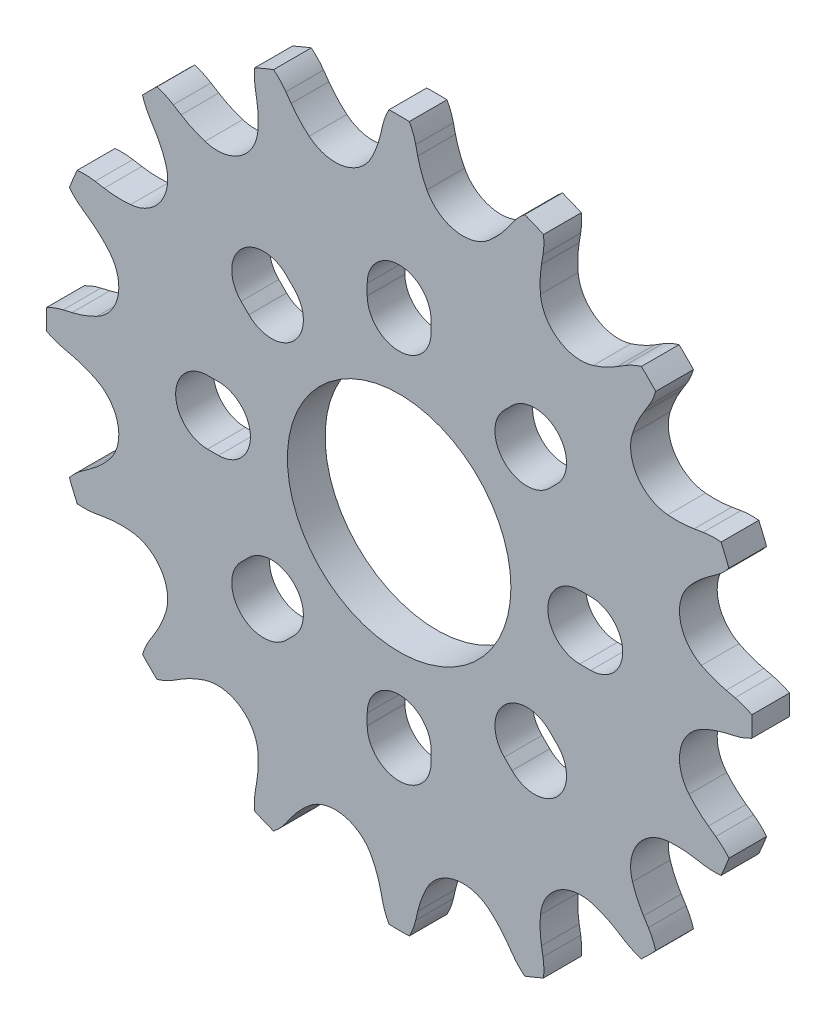
SolidWorks part; units mm, degrees
ref_plane "Front" through (0, 0, 0) normal (0, 0, 1) x (1, 0, 0)
ref_plane "Top" through (0, 0, 0) normal (0, 1, 0) x (1, 0, 0)
ref_plane "Right" through (0, 0, 0) normal (1, 0, 0) x (0, 0, -1)
ref_plane "Plane1" through (0, 0, -0.3201) normal (0, 0, -1) x (-1, 0, 0)
sketch "Sketch1" plane through (0, 0, -0.3201) normal (0, 0, -1) x (-1, 0, 0)
  line L0 (19.3696, 6.7618) -> (19.8362, 7.0946)
  line L1 (19.043, 9.0096) -> (18.4777, 8.9151)
  line L2 (15.3075, 13.6595) -> (15.6113, 14.1456)
  line L3 (14.1456, 15.6113) -> (13.6595, 15.3075)
  line L4 (8.9151, 18.4777) -> (9.0096, 19.043)
  line L5 (7.0946, 19.8362) -> (6.7618, 19.3696)
  line L6 (1.1653, 20.4828) -> (1.0364, 21.0412)
  line L7 (-1.0364, 21.0412) -> (-1.1653, 20.4828)
  line L8 (-6.7618, 19.3696) -> (-7.0946, 19.8362)
  line L9 (-9.0096, 19.043) -> (-8.9151, 18.4777)
  line L10 (-13.6595, 15.3075) -> (-14.1456, 15.6113)
  line L11 (-15.6113, 14.1456) -> (-15.3075, 13.6595)
  line L12 (-18.4777, 8.9151) -> (-19.043, 9.0096)
  line L13 (-19.8362, 7.0946) -> (-19.3696, 6.7618)
  line L14 (-20.4828, 1.1653) -> (-21.0412, 1.0364)
  line L15 (-21.0412, -1.0364) -> (-20.4828, -1.1653)
  line L16 (-19.3696, -6.7618) -> (-19.8362, -7.0946)
  line L17 (-19.043, -9.0096) -> (-18.4777, -8.9151)
  line L18 (-15.3075, -13.6595) -> (-15.6113, -14.1456)
  line L19 (-14.1456, -15.6113) -> (-13.6595, -15.3075)
  line L20 (-8.9151, -18.4777) -> (-9.0096, -19.043)
  line L21 (-7.0946, -19.8362) -> (-6.7618, -19.3696)
  line L22 (-1.1653, -20.4828) -> (-1.0364, -21.0412)
  line L23 (1.0364, -21.0412) -> (1.1653, -20.4828)
  line L24 (6.7618, -19.3696) -> (7.0946, -19.8362)
  line L25 (9.0096, -19.043) -> (8.9151, -18.4777)
  line L26 (13.6595, -15.3075) -> (14.1456, -15.6113)
  line L27 (15.6113, -14.1456) -> (15.3075, -13.6595)
  line L28 (18.4777, -8.9151) -> (19.043, -9.0096)
  line L29 (19.8362, -7.0946) -> (19.3696, -6.7618)
  line L30 (20.4828, -1.1653) -> (21.0412, -1.0364)
  line L31 (21.0412, 1.0364) -> (20.4828, 1.1653)
  line L32 (-2, 11.3137) -> (-2, 12)
  line L33 (2, 12) -> (2, 11.3137)
  line L34 (6.5858, 9.4142) -> (7.0711, 9.8995)
  line L35 (9.8995, 7.0711) -> (9.4142, 6.5858)
  line L36 (-9.4142, 6.5858) -> (-9.8995, 7.0711)
  line L37 (-7.0711, 9.8995) -> (-6.5858, 9.4142)
  line L38 (-11.3137, -2) -> (-12, -2)
  line L39 (-12, 2) -> (-11.3137, 2)
  line L40 (-9.8995, -7.0711) -> (-9.4142, -6.5858)
  line L41 (-6.5858, -9.4142) -> (-7.0711, -9.8995)
  line L42 (2, -11.3137) -> (2, -12)
  line L43 (-2, -12) -> (-2, -11.3137)
  line L44 (9.4142, -6.5858) -> (9.8995, -7.0711)
  line L45 (7.0711, -9.8995) -> (6.5858, -9.4142)
  line L46 (11.3137, 2) -> (12, 2)
  line L47 (12, -2) -> (11.3137, -2)
  arc A0 (18.1555, 5.6395) -> (19.3696, 6.7618) centre (23.1735, 1.4288) cw
  arc A1 (19.8362, 7.0946) -> (20.6534, 7.8644) centre (17.4306, 10.4672) ccw
  arc A2 (20.6534, 7.8644) -> (20.1651, 9.0432) centre (0, 0) ccw
  arc A3 (20.1651, 9.0432) -> (19.043, 9.0096) centre (19.7267, 4.9239) ccw
  arc A4 (18.4777, 8.9151) -> (16.8256, 8.8501) centre (17.3965, 15.3758) cw
  arc A5 (16.8256, 8.8501) -> (14.6153, 12.158) centre (17.0479, 11.391) cw
  arc A6 (14.6153, 12.158) -> (15.3075, 13.6595) centre (20.8628, 10.1882) cw
  arc A7 (15.6113, 14.1456) -> (16.0717, 15.1694) centre (12.0981, 16.3408) ccw
  arc A8 (16.0717, 15.1694) -> (15.1694, 16.0717) centre (0, 0) ccw
  arc A9 (15.1694, 16.0717) -> (14.1456, 15.6113) centre (16.3408, 12.0981) ccw
  arc A10 (13.6595, 15.3075) -> (12.158, 14.6153) centre (10.1882, 20.8628) cw
  arc A11 (12.158, 14.6153) -> (8.8501, 16.8256) centre (11.391, 17.0479) cw
  arc A12 (8.8501, 16.8256) -> (8.9151, 18.4777) centre (15.3758, 17.3965) cw
  arc A13 (9.0096, 19.043) -> (9.0432, 20.1651) centre (4.9239, 19.7267) ccw
  arc A14 (9.0432, 20.1651) -> (7.8644, 20.6534) centre (0, 0) ccw
  arc A15 (7.8644, 20.6534) -> (7.0946, 19.8362) centre (10.4672, 17.4306) ccw
  arc A16 (6.7618, 19.3696) -> (5.6395, 18.1555) centre (1.4288, 23.1735) cw
  arc A17 (5.6395, 18.1555) -> (1.7376, 18.9316) centre (4, 20.1094) cw
  arc A18 (1.7376, 18.9316) -> (1.1653, 20.4828) centre (7.548, 21.9564) cw
  arc A19 (1.0364, 21.0412) -> (0.638, 22.0908) centre (-3, 20.1094) ccw
  arc A20 (0.638, 22.0908) -> (-0.638, 22.0908) centre (0, 0) ccw
  arc A21 (-0.638, 22.0908) -> (-1.0364, 21.0412) centre (3, 20.1094) ccw
  arc A22 (-1.1653, 20.4828) -> (-1.7376, 18.9316) centre (-7.548, 21.9564) cw
  arc A23 (-1.7376, 18.9316) -> (-5.6395, 18.1555) centre (-4, 20.1094) cw
  arc A24 (-5.6395, 18.1555) -> (-6.7618, 19.3696) centre (-1.4288, 23.1735) cw
  arc A25 (-7.0946, 19.8362) -> (-7.8644, 20.6534) centre (-10.4672, 17.4306) ccw
  arc A26 (-7.8644, 20.6534) -> (-9.0432, 20.1651) centre (0, 0) ccw
  arc A27 (-9.0432, 20.1651) -> (-9.0096, 19.043) centre (-4.9239, 19.7267) ccw
  arc A28 (-8.9151, 18.4777) -> (-8.8501, 16.8256) centre (-15.3758, 17.3965) cw
  arc A29 (-8.8501, 16.8256) -> (-12.158, 14.6153) centre (-11.391, 17.0479) cw
  arc A30 (-12.158, 14.6153) -> (-13.6595, 15.3075) centre (-10.1882, 20.8628) cw
  arc A31 (-14.1456, 15.6113) -> (-15.1694, 16.0717) centre (-16.3408, 12.0981) ccw
  arc A32 (-15.1694, 16.0717) -> (-16.0717, 15.1694) centre (0, 0) ccw
  arc A33 (-16.0717, 15.1694) -> (-15.6113, 14.1456) centre (-12.0981, 16.3408) ccw
  arc A34 (-15.3075, 13.6595) -> (-14.6153, 12.158) centre (-20.8628, 10.1882) cw
  arc A35 (-14.6153, 12.158) -> (-16.8256, 8.8501) centre (-17.0479, 11.391) cw
  arc A36 (-16.8256, 8.8501) -> (-18.4777, 8.9151) centre (-17.3965, 15.3758) cw
  arc A37 (-19.043, 9.0096) -> (-20.1651, 9.0432) centre (-19.7267, 4.9239) ccw
  arc A38 (-20.1651, 9.0432) -> (-20.6534, 7.8644) centre (0, 0) ccw
  arc A39 (-20.6534, 7.8644) -> (-19.8362, 7.0946) centre (-17.4306, 10.4672) ccw
  arc A40 (-19.3696, 6.7618) -> (-18.1555, 5.6395) centre (-23.1735, 1.4288) cw
  arc A41 (-18.1555, 5.6395) -> (-18.9316, 1.7376) centre (-20.1094, 4) cw
  arc A42 (-18.9316, 1.7376) -> (-20.4828, 1.1653) centre (-21.9564, 7.548) cw
  arc A43 (-21.0412, 1.0364) -> (-22.0908, 0.638) centre (-20.1094, -3) ccw
  arc A44 (-22.0908, 0.638) -> (-22.0908, -0.638) centre (0, 0) ccw
  arc A45 (-22.0908, -0.638) -> (-21.0412, -1.0364) centre (-20.1094, 3) ccw
  arc A46 (-20.4828, -1.1653) -> (-18.9316, -1.7376) centre (-21.9564, -7.548) cw
  arc A47 (-18.9316, -1.7376) -> (-18.1555, -5.6395) centre (-20.1094, -4) cw
  arc A48 (-18.1555, -5.6395) -> (-19.3696, -6.7618) centre (-23.1735, -1.4288) cw
  arc A49 (-19.8362, -7.0946) -> (-20.6534, -7.8644) centre (-17.4306, -10.4672) ccw
  arc A50 (-20.6534, -7.8644) -> (-20.1651, -9.0432) centre (0, 0) ccw
  arc A51 (-20.1651, -9.0432) -> (-19.043, -9.0096) centre (-19.7267, -4.9239) ccw
  arc A52 (-18.4777, -8.9151) -> (-16.8256, -8.8501) centre (-17.3965, -15.3758) cw
  arc A53 (-16.8256, -8.8501) -> (-14.6153, -12.158) centre (-17.0479, -11.391) cw
  arc A54 (-14.6153, -12.158) -> (-15.3075, -13.6595) centre (-20.8628, -10.1882) cw
  arc A55 (-15.6113, -14.1456) -> (-16.0717, -15.1694) centre (-12.0981, -16.3408) ccw
  arc A56 (-16.0717, -15.1694) -> (-15.1694, -16.0717) centre (0, 0) ccw
  arc A57 (-15.1694, -16.0717) -> (-14.1456, -15.6113) centre (-16.3408, -12.0981) ccw
  arc A58 (-13.6595, -15.3075) -> (-12.158, -14.6153) centre (-10.1882, -20.8628) cw
  arc A59 (-12.158, -14.6153) -> (-8.8501, -16.8256) centre (-11.391, -17.0479) cw
  arc A60 (-8.8501, -16.8256) -> (-8.9151, -18.4777) centre (-15.3758, -17.3965) cw
  arc A61 (-9.0096, -19.043) -> (-9.0432, -20.1651) centre (-4.9239, -19.7267) ccw
  arc A62 (-9.0432, -20.1651) -> (-7.8644, -20.6534) centre (0, 0) ccw
  arc A63 (-7.8644, -20.6534) -> (-7.0946, -19.8362) centre (-10.4672, -17.4306) ccw
  arc A64 (-6.7618, -19.3696) -> (-5.6395, -18.1555) centre (-1.4288, -23.1735) cw
  arc A65 (-5.6395, -18.1555) -> (-1.7376, -18.9316) centre (-4, -20.1094) cw
  arc A66 (-1.7376, -18.9316) -> (-1.1653, -20.4828) centre (-7.548, -21.9564) cw
  arc A67 (-1.0364, -21.0412) -> (-0.638, -22.0908) centre (3, -20.1094) ccw
  arc A68 (-0.638, -22.0908) -> (0.638, -22.0908) centre (0, 0) ccw
  arc A69 (0.638, -22.0908) -> (1.0364, -21.0412) centre (-3, -20.1094) ccw
  arc A70 (1.1653, -20.4828) -> (1.7376, -18.9316) centre (7.548, -21.9564) cw
  arc A71 (1.7376, -18.9316) -> (5.6395, -18.1555) centre (4, -20.1094) cw
  arc A72 (5.6395, -18.1555) -> (6.7618, -19.3696) centre (1.4288, -23.1735) cw
  arc A73 (7.0946, -19.8362) -> (7.8644, -20.6534) centre (10.4672, -17.4306) ccw
  arc A74 (7.8644, -20.6534) -> (9.0432, -20.1651) centre (0, 0) ccw
  arc A75 (9.0432, -20.1651) -> (9.0096, -19.043) centre (4.9239, -19.7267) ccw
  arc A76 (8.9151, -18.4777) -> (8.8501, -16.8256) centre (15.3758, -17.3965) cw
  arc A77 (8.8501, -16.8256) -> (12.158, -14.6153) centre (11.391, -17.0479) cw
  arc A78 (12.158, -14.6153) -> (13.6595, -15.3075) centre (10.1882, -20.8628) cw
  arc A79 (14.1456, -15.6113) -> (15.1694, -16.0717) centre (16.3408, -12.0981) ccw
  arc A80 (15.1694, -16.0717) -> (16.0717, -15.1694) centre (0, 0) ccw
  arc A81 (16.0717, -15.1694) -> (15.6113, -14.1456) centre (12.0981, -16.3408) ccw
  arc A82 (15.3075, -13.6595) -> (14.6153, -12.158) centre (20.8628, -10.1882) cw
  arc A83 (14.6153, -12.158) -> (16.8256, -8.8501) centre (17.0479, -11.391) cw
  arc A84 (16.8256, -8.8501) -> (18.4777, -8.9151) centre (17.3965, -15.3758) cw
  arc A85 (19.043, -9.0096) -> (20.1651, -9.0432) centre (19.7267, -4.9239) ccw
  arc A86 (20.1651, -9.0432) -> (20.6534, -7.8644) centre (0, 0) ccw
  arc A87 (20.6534, -7.8644) -> (19.8362, -7.0946) centre (17.4306, -10.4672) ccw
  arc A88 (19.3696, -6.7618) -> (18.1555, -5.6395) centre (23.1735, -1.4288) cw
  arc A89 (18.1555, -5.6395) -> (18.9316, -1.7376) centre (20.1094, -4) cw
  arc A90 (18.9316, -1.7376) -> (20.4828, -1.1653) centre (21.9564, -7.548) cw
  arc A91 (21.0412, -1.0364) -> (22.0908, -0.638) centre (20.1094, 3) ccw
  arc A92 (22.0908, -0.638) -> (22.0908, 0.638) centre (0, 0) ccw
  arc A93 (22.0908, 0.638) -> (21.0412, 1.0364) centre (20.1094, -3) ccw
  arc A94 (20.4828, 1.1653) -> (18.9316, 1.7376) centre (21.9564, 7.548) cw
  arc A95 (18.9316, 1.7376) -> (18.1555, 5.6395) centre (20.1094, 4) cw
  circle A96 centre (0, 0) radius 7
  arc A97 (-2, 12) -> (2, 12) centre (0, 12) cw
  arc A98 (2, 11.3137) -> (-2, 11.3137) centre (0, 11.3137) cw
  arc A99 (7.0711, 9.8995) -> (9.8995, 7.0711) centre (8.4853, 8.4853) cw
  arc A100 (9.4142, 6.5858) -> (6.5858, 9.4142) centre (8, 8) cw
  arc A101 (-9.8995, 7.0711) -> (-7.0711, 9.8995) centre (-8.4853, 8.4853) cw
  arc A102 (-6.5858, 9.4142) -> (-9.4142, 6.5858) centre (-8, 8) cw
  arc A103 (-12, -2) -> (-12, 2) centre (-12, 0) cw
  arc A104 (-11.3137, 2) -> (-11.3137, -2) centre (-11.3137, 0) cw
  arc A105 (-7.0711, -9.8995) -> (-9.8995, -7.0711) centre (-8.4853, -8.4853) cw
  arc A106 (-9.4142, -6.5858) -> (-6.5858, -9.4142) centre (-8, -8) cw
  arc A107 (2, -12) -> (-2, -12) centre (0, -12) cw
  arc A108 (-2, -11.3137) -> (2, -11.3137) centre (0, -11.3137) cw
  arc A109 (9.8995, -7.0711) -> (7.0711, -9.8995) centre (8.4853, -8.4853) cw
  arc A110 (6.5858, -9.4142) -> (9.4142, -6.5858) centre (8, -8) cw
  arc A111 (12, 2) -> (12, -2) centre (12, 0) cw
  arc A112 (11.3137, -2) -> (11.3137, 2) centre (11.3137, 0) cw
extrude "Boss-Extrude1" add sketch "Sketch1" against normal blind 2.3622
